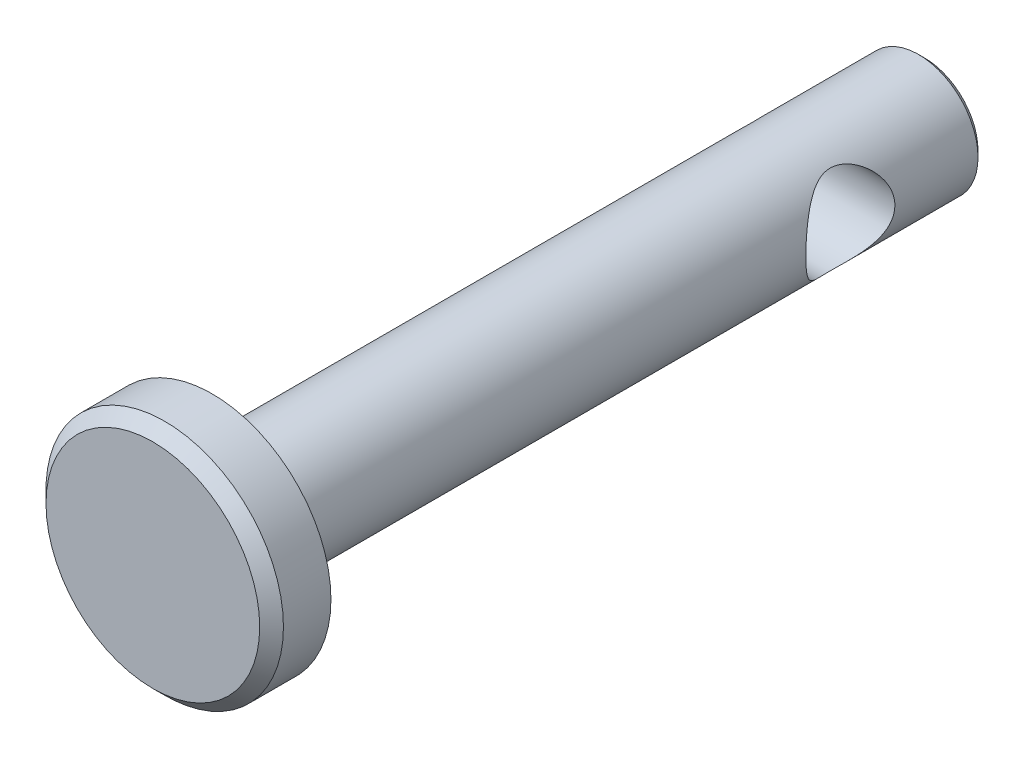
SolidWorks part; units mm, degrees
ref_plane "Front" through (0, 0, 0) normal (0, 0, 1) x (1, 0, 0)
ref_plane "Top" through (0, 0, 0) normal (0, 1, 0) x (1, 0, 0)
ref_plane "Right" through (0, 0, 0) normal (1, 0, 0) x (0, 0, -1)
sketch "Sketch1" plane through (0, 0, 0) normal (0, 0, 1) x (1, 0, 0)
  circle A0 centre (0, 0) radius 1.5875
  point P3 (0, 1.5875)
  point P4 (0, -1.5875)
  dimension "dia" = 3.175
extrude "Extrude1" add sketch "Sketch1" along normal mid plane 19.05
sketch "Sketch2" plane through (0, 0, 9.525) normal (0, 0, 1) x (1, 0, 0)
  circle A0 centre (0, 0) radius 3.175
  dimension "head dia" = 6.35
extrude "Extrude2" add sketch "Sketch2" along normal blind 1.5875
chamfer "Chamfer1" distance 0.3175 angle 45 1 edges at (3.175, 0, 11.1125)
sketch "Sketch3" plane through (0, 0, 0) normal (1, 0, 0) x (0, 0, -1)
  line L0 (-9.525, -1.5875) -> (-9.525, 1.5875) construction
  circle A0 centre (5.9531, 0) radius 1.1906
  point P2 (4.7625, 0)
  dimension "hole dia" = 2.3813
  dimension "useable Lg" = 14.2875
extrude "Extrude3" cut sketch "Sketch3" against normal through all and the other way through all
chamfer "Chamfer2" distance 0.1588 angle 45 1 edges at (1.5875, 0, -9.525)
ref_plane "Plane1" through (0, 0, -5.9531) normal (0, 0, 1) x (1, 0, 0)
sketch "Sketch8" plane through (0, 0, 0) normal (1, 0, 0) x (0, 0, -1)
  line L0 (-11.1125, 2.8575) -> (-11.1125, -2.8575) construction
  line L1 (-10.795, -3.175) -> (-9.525, -3.175) construction
  line L2 (9.525, -1.4287) -> (9.525, 1.4287) construction
  point P0 (-11.1125, 3.175)
  point P1 (-9.525, 3.175)
  point P5 (9.525, 1.5875)
  point P8 (-11.1125, -3.175)
  point P9 (9.525, -1.5875)
equation "\"D1@Chamfer1\" = \"head ht@Extrude2\" * .2"
equation "\"D1@Chamfer2\" = \"dia@Sketch1\" * .05"
